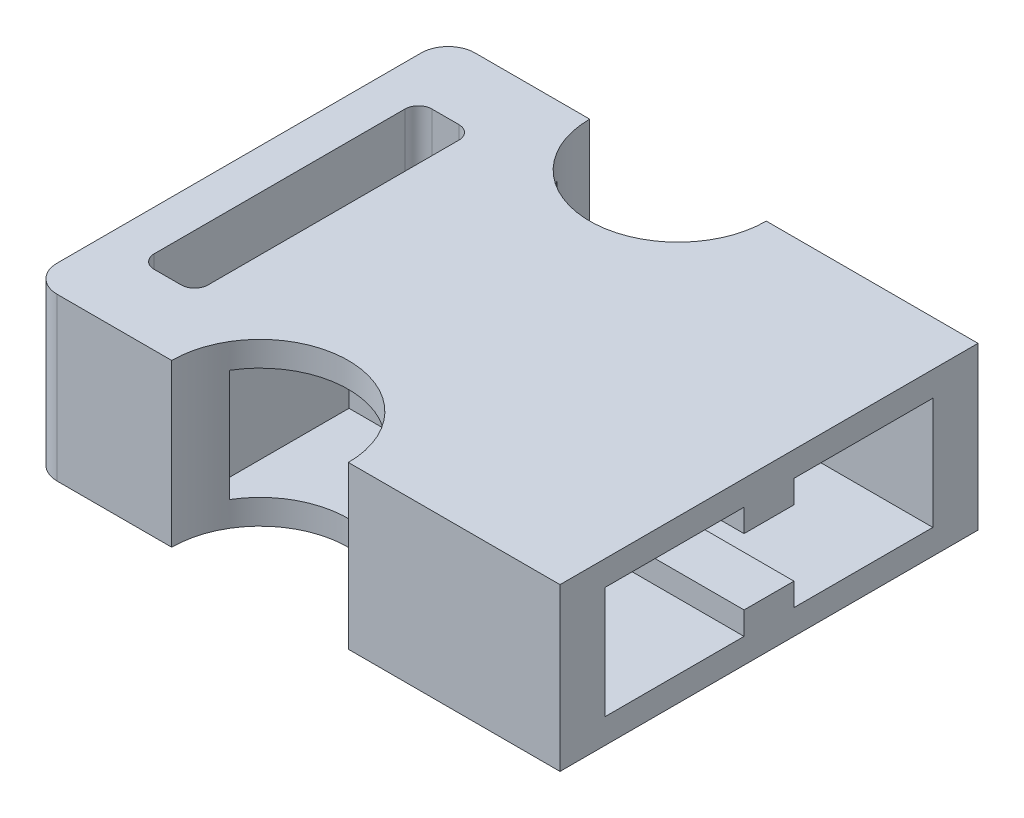
SolidWorks part; units mm, degrees
ref_plane "Front Plane" through (0, 0, 0) normal (0, 0, 1) x (1, 0, 0)
ref_plane "Top Plane" through (0, 0, 0) normal (0, 1, 0) x (1, 0, 0)
ref_plane "Right Plane" through (0, 0, 0) normal (1, 0, 0) x (0, 0, -1)
sketch "Sketch3" plane through (0, 0, 0) normal (0, 1, 0) x (1, 0, 0)
  line L0 (6.35, 32.766) -> (6.35, 6.604) construction
  line L1 (2.54, 0) -> (10.16, 0)
  line L2 (0, 2.54) -> (0, 36.83)
  line L3 (2.54, 39.37) -> (10.16, 39.37)
  line L4 (12.7, 2.54) -> (12.7, 36.83)
  line L5 (3.81, 19.685) -> (8.89, 19.685) construction
  line L6 (5.08, 6.604) -> (7.62, 6.604)
  line L7 (5.08, 32.766) -> (7.62, 32.766)
  line L8 (3.81, 31.496) -> (3.81, 7.874)
  line L9 (8.89, 31.496) -> (8.89, 7.874)
  line L10 (8.89, 39.37) -> (8.89, 0) construction
  line L11 (6.35, 39.37) -> (6.35, 0) construction
  line L12 (3.81, 39.37) -> (3.81, 0) construction
  line L13 (0, 32.766) -> (19.05, 32.766) construction
  line L14 (0, 19.685) -> (19.05, 19.685) construction
  line L15 (0, 6.604) -> (19.05, 6.604) construction
  line L16 (6.35, 39.37) -> (6.35, 0) construction
  line L17 (10.16, 39.37) -> (12.7, 39.37)
  line L18 (12.7, 36.83) -> (12.7, 39.37)
  line L19 (12.7, 2.54) -> (12.7, 0)
  line L20 (10.16, 0) -> (12.7, 0)
  arc A0 (0, 2.54) -> (2.54, 0) centre (2.54, 2.54) ccw
  arc A3 (2.54, 39.37) -> (0, 36.83) centre (2.54, 36.83) ccw
  arc A4 (3.81, 7.874) -> (5.08, 6.604) centre (5.08, 7.874) ccw
  arc A5 (7.62, 6.604) -> (8.89, 7.874) centre (7.62, 7.874) ccw
  arc A6 (8.89, 31.496) -> (7.62, 32.766) centre (7.62, 31.496) ccw
  arc A7 (5.08, 32.766) -> (3.81, 31.496) centre (5.08, 31.496) ccw
  point P29 (0, 0)
  point P34 (12.7, 39.37)
  point P37 (0, 39.37)
  dimension "D7" = 2.54
  dimension "D8" = 1.27
  dimension "D1" = 39.37
  dimension "D2" = 12.7
  dimension "D3" = 13.081
  dimension "D4" = 13.081
  dimension "D5" = 2.54
  dimension "D6" = 2.54
extrude "Boss-Extrude1" add sketch "Sketch3" along normal blind 15.24
sketch "Sketch4" plane through (0, 0, 0) normal (0, 1, 0) x (1, 0, 0)
  line L0 (-6.985, 0) -> (6.985, 0) construction
  line L1 (12.7, 39.37) -> (13.335, 39.37)
  line L2 (12.7, 39.37) -> (12.7, 0)
  line L3 (12.7, 0) -> (13.335, 0)
  line L4 (49.911, 39.37) -> (49.911, 0)
  line L5 (12.7, 19.685) -> (49.911, 19.685) construction
  line L6 (27.051, 39.37) -> (27.051, 23.158) construction
  line L7 (29.972, 39.37) -> (29.972, 24.6438) construction
  line L8 (13.335, 39.37) -> (13.335, 6.7029) construction
  line L9 (29.972, 39.37) -> (49.911, 39.37)
  line L10 (29.972, 0) -> (49.911, 0)
  arc A3 (13.335, 39.37) -> (29.972, 39.37) centre (21.6535, 39.37) ccw
  arc A4 (13.335, 0) -> (29.972, 0) centre (21.6535, 0) cw
  dimension "D1" = 37.211
  dimension "D2" = 22.86
  dimension "D3" = 19.939
  dimension "D4" = 16.637
extrude "Boss-Extrude2" add sketch "Sketch4" along normal blind 15.24
ref_plane "Plane1" through (0, 7.62, 0) normal (0, 1, 0) x (1, 0, 0)
sketch "Sketch6" plane through (0, 7.62, 0) normal (0, 1, 0) x (1, 0, 0)
  line L0 (49.911, 19.685) -> (0, 19.685) construction
  line L1 (49.911, 0) -> (49.911, 39.37) construction
  line L2 (0, -8.382) -> (0, 8.382) construction
  line L3 (49.911, 35.1155) -> (12.7, 35.1155)
  line L4 (49.911, 4.2545) -> (12.7, 4.2545)
  line L5 (12.7, 35.1155) -> (12.7, 4.2545)
  line L6 (49.911, 35.1155) -> (0, 35.1155) construction
  line L7 (49.911, 4.2545) -> (0, 4.2545) construction
  line L8 (49.911, 35.1155) -> (49.911, 4.2545)
  dimension "D3" = 12.7
  dimension "D1" = 15.4305
  dimension "D2" = 15.4305
extrude "Cut-Extrude1" cut sketch "Sketch6" against normal mid plane 10.541
sketch "Sketch7" plane through (0, 2.3495, 0) normal (0, 1, 0) x (1, 0, 0)
  line L0 (12.7, 22.0345) -> (12.7, 17.3355)
  line L4 (12.7, 19.685) -> (49.911, 19.685) construction
  line L5 (49.911, 0) -> (49.911, 39.37) construction
  line L6 (12.7, 17.3355) -> (49.911, 17.3355)
  line L7 (12.7, 22.0345) -> (49.911, 22.0345)
  line L8 (49.911, 17.3355) -> (49.911, 22.0345)
  dimension "D2" = 2.3495
  dimension "D3" = 2.3495
extrude "Boss-Extrude3" add sketch "Sketch7" along normal blind 2.159
mirror "Mirror1" about plane through (0, 7.62, 0) normal (0, 1, 0) of "Boss-Extrude3"
